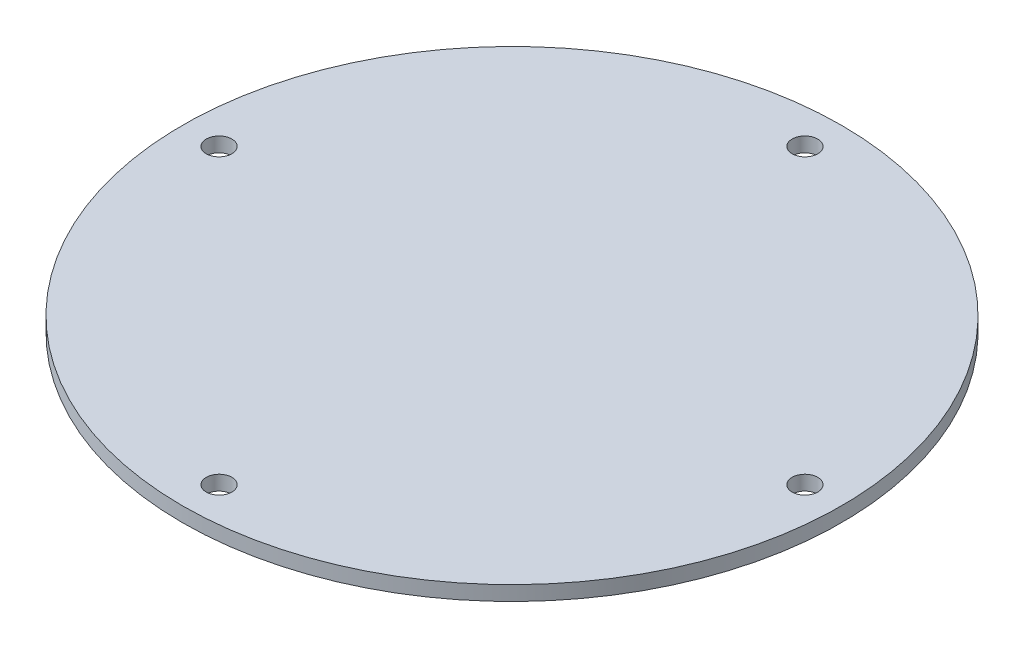
SolidWorks part; units mm, degrees
ref_plane "Front Plane" through (0, 0, 0) normal (0, 0, 1) x (1, 0, 0)
ref_plane "Top Plane" through (0, 0, 0) normal (0, 1, 0) x (1, 0, 0)
ref_plane "Right Plane" through (0, 0, 0) normal (1, 0, 0) x (0, 0, -1)
sketch "Sketch1" plane through (0, 0, 0) normal (0, 1, 0) x (1, 0, 0)
  circle A0 centre (0, 0) radius 45
  dimension "D1" = 90
extrude "Boss-Extrude1" add sketch "Sketch1" along normal blind 2
sketch "Sketch3" plane through (0, 2, 0) normal (0, 1, 0) x (1, 0, 0)
  circle A0 centre (0, 40) radius 1.75
  circle A1 centre (40, 0) radius 1.75
  circle A2 centre (0, -40) radius 1.75
  circle A3 centre (-40, 0) radius 1.75
  point P2 (0, 0)
  dimension "D2" = 3.5
  dimension "D1" = 40
  dimension "D3" = 4
extrude "Cut-Extrude1" cut sketch "Sketch3" against normal through all
